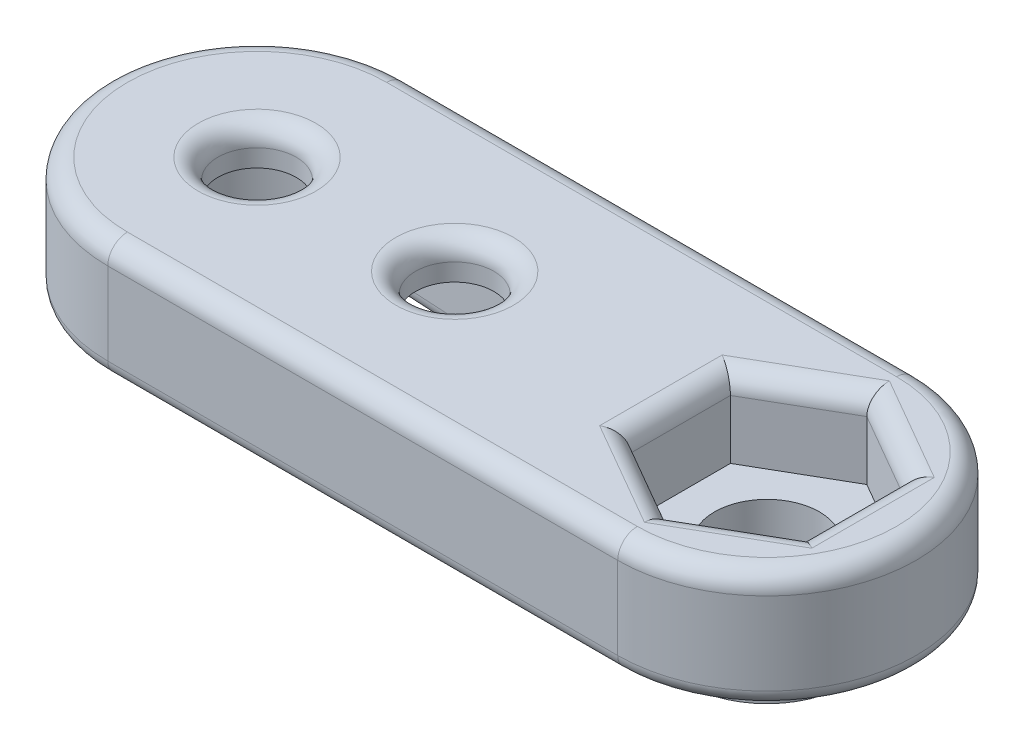
SolidWorks part; units mm, degrees
ref_plane "Front Plane" through (0, 0, 0) normal (0, 0, 1) x (1, 0, 0)
ref_plane "Top Plane" through (0, 0, 0) normal (0, 1, 0) x (1, 0, 0)
ref_plane "Right Plane" through (0, 0, 0) normal (1, 0, 0) x (0, 0, -1)
sketch "Sketch1" plane through (0, 0, 0) normal (0, 1, 0) x (1, 0, 0)
  line L0 (2.2864, 2.65) -> (14.1103, 1.997)
  line L1 (2.2864, -2.65) -> (14.1103, -1.997)
  line L2 (0, 0) -> (14, 0) construction
  line L4 (0, 6.04) -> (20.6375, 6.04)
  line L5 (24.1375, -2.0207) -> (24.1375, 2.0207)
  line L8 (0, -6.04) -> (20.6375, -6.04)
  line L9 (24.1375, 2.0207) -> (20.6375, 4.0415)
  line L10 (20.6375, 4.0415) -> (17.1375, 2.0207)
  line L11 (17.1375, 2.0207) -> (17.1375, -2.0207)
  line L12 (17.1375, -2.0207) -> (20.6375, -4.0415)
  line L13 (20.6375, -4.0415) -> (24.1375, -2.0207)
  circle A0 centre (0, 0) radius 3.5 construction
  arc A1 (14.1103, 1.997) -> (14.1103, -1.997) centre (14, 0) cw
  arc A2 (2.2864, 2.65) -> (2.2864, -2.65) centre (0, 0) ccw
  circle A3 centre (14, 0) radius 0.5 construction
  circle A4 centre (12, 0) radius 0.5 construction
  circle A5 centre (10, 0) radius 0.5 construction
  circle A6 centre (8, 0) radius 0.5 construction
  circle A7 centre (6, 0) radius 0.5 construction
  circle A8 centre (4, 0) radius 0.5 construction
  arc A12 (0, -6.04) -> (0, 6.04) centre (0, 0) cw
  circle A17 centre (20.6375, 0) radius 4.064 construction
  arc A18 (20.6375, -6.04) -> (20.6375, 6.04) centre (20.6375, 0) ccw
  circle A19 centre (20.6375, 0) radius 3.5 construction
  point P4 (16, 0)
  point P6 (-3.5, 0)
  point P12 (21.1873, 0)
  dimension "D1" = 7
  dimension "D5" = 1
  dimension "D8" = 2.54
  dimension "D10" = 20.6375
  dimension "D4" = 2
  dimension "D9" = 8.128
  dimension "D2" = 19.5
  dimension "D3" = 5.3
  dimension "D7" = 2
  dimension "D11" = 7
  dimension "D6" = 6
extrude "Boss-Extrude1" add sketch "Sketch1" along normal blind 4.5
sketch "Sketch2" plane through (0, 4.5, 0) normal (0, 1, 0) x (1, 0, 0)
  line L0 (0, 0) -> (16, 0) construction
  line L1 (24.1375, 2.0207) -> (20.6375, 4.0415) construction
  line L2 (20.6375, 4.0415) -> (17.1375, 2.0207) construction
  line L3 (17.1375, 2.0207) -> (17.1375, -2.0207) construction
  line L4 (20.6375, 6.04) -> (0, 6.04)
  line L5 (0, -6.04) -> (20.6375, -6.04)
  line L6 (17.1375, -2.0207) -> (20.6375, -4.0415) construction
  line L7 (20.6375, -4.0415) -> (24.1375, -2.0207) construction
  line L8 (20.6375, 6.04) -> (0, 6.04)
  line L9 (0, -6.04) -> (20.6375, -6.04)
  line L10 (24.1375, -2.0207) -> (24.1375, 2.0207) construction
  line L11 (24.1375, 2.0207) -> (20.6375, 4.0415)
  line L12 (20.6375, 4.0415) -> (17.1375, 2.0207)
  line L13 (17.1375, 2.0207) -> (17.1375, -2.0207)
  line L14 (17.1375, -2.0207) -> (20.6375, -4.0415)
  line L15 (20.6375, -4.0415) -> (24.1375, -2.0207)
  line L16 (24.1375, -2.0207) -> (24.1375, 2.0207)
  circle A0 centre (0, 0) radius 1.5875
  circle A1 centre (8, 0) radius 1.5875
  arc A2 (14.1103, -1.997) -> (14.1103, 1.997) centre (14, 0) ccw construction
  arc A5 (20.6375, -6.04) -> (20.6375, 6.04) centre (20.6375, 0) ccw
  arc A6 (20.6375, -6.04) -> (20.6375, 6.04) centre (20.6375, 0) ccw
  arc A9 (0, 6.04) -> (0, -6.04) centre (0, 0) ccw
  arc A17 (0, 6.04) -> (0, -6.04) centre (0, 0) ccw
  point P15 (8, 0)
  dimension "D2" = 3.175
  dimension "D3" = 3.175
  dimension "D1" = 0
extrude "Boss-Extrude2" add sketch "Sketch2" along normal offset from surface (1.5 mm away) 6 up to face at (10.3187, 0, 0)
sketch "Sketch3" plane through (0, 0, 0) normal (0, -1, 0) x (1, 0, 0)
  line L6 (20.6375, 6.04) -> (0, 6.04)
  line L7 (0, -6.04) -> (20.6375, -6.04)
  line L10 (20.6375, 6.04) -> (0, 6.04)
  line L11 (0, -6.04) -> (20.6375, -6.04)
  arc A2 (20.6375, -6.04) -> (20.6375, 6.04) centre (20.6375, 0) ccw
  arc A3 (20.6375, -6.04) -> (20.6375, 6.04) centre (20.6375, 0) ccw
  arc A11 (0, 6.04) -> (0, -6.04) centre (0, 0) ccw
  arc A17 (0, 6.04) -> (0, -6.04) centre (0, 0) ccw
  dimension "D1" = 0
extrude "Cut-Extrude1" cut sketch "Sketch3" against normal offset from surface (1.2375 mm away) 4.7625 up to face at (8, 6, -1.5875)
sketch "Sketch5" plane through (0, 1.2375, 0) normal (0, 1, 0) x (1, 0, 0)
  line L0 (20.6375, 4.0415) -> (24.1375, 2.0207) construction
  line L1 (17.1375, 2.0207) -> (20.6375, 4.0415) construction
  line L2 (17.1375, -2.0207) -> (17.1375, 2.0207) construction
  line L3 (20.6375, -4.0415) -> (17.1375, -2.0207) construction
  line L4 (24.1375, -2.0207) -> (20.6375, -4.0415) construction
  line L5 (24.1375, 2.0207) -> (24.1375, -2.0207) construction
  line L6 (20.6375, 4.0415) -> (24.1375, 2.0207)
  line L7 (17.1375, 2.0207) -> (20.6375, 4.0415)
  line L8 (17.1375, -2.0207) -> (17.1375, 2.0207)
  line L9 (20.6375, -4.0415) -> (17.1375, -2.0207)
  line L10 (24.1375, -2.0207) -> (20.6375, -4.0415)
  line L11 (24.1375, 2.0207) -> (24.1375, -2.0207)
  line L12 (17.1375, 2.0207) -> (24.1375, -2.0207) construction
  circle A0 centre (20.6375, 0) radius 2.125
  point P5 (20.6375, 0)
  dimension "D1" = 4.25
extrude "Boss-Extrude4" add sketch "Sketch5" along normal blind 1.5875
sketch "Sketch4" plane through (0, 6, 0) normal (0, 1, 0) x (1, 0, 0)
  circle A0 centre (20.6375, 0) radius 3.25
  circle A1 centre (20.6375, 0) radius 2.125
  circle A3 centre (20.6375, 0) radius 2.125 construction
  dimension "D1" = 6.5
extrude "Boss-Extrude3" add sketch "Sketch4" against normal blind 1.778 from surface
fillet "Fillet2" radius 0.635 9 edges at (10.3187, 1.2375, -6.04) (-6.04, 1.2375, 0) (10.3187, 1.2375, 6.04) (-3.5, 1.2375, 0) (8.1983, 1.2375, -2.3235) (16, 1.2375, 0) (8.1983, 1.2375, 2.3235) (26.6775, 1.2375, 0) (20.6375, 1.2375, -3.25)
fillet "Fillet3" radius 0.7937 12 edges at (10.3187, 6, 6.04) (-6.04, 6, 0) (10.3187, 6, -6.04) (0, 6, -1.5875) (8, 6, -1.5875) (26.6775, 6, 0) (22.3875, 6, -3.0311) (18.8875, 6, -3.0311) (17.1375, 6, 0) (18.8875, 6, 3.0311) (22.3875, 6, 3.0311) (24.1375, 6, 0)
